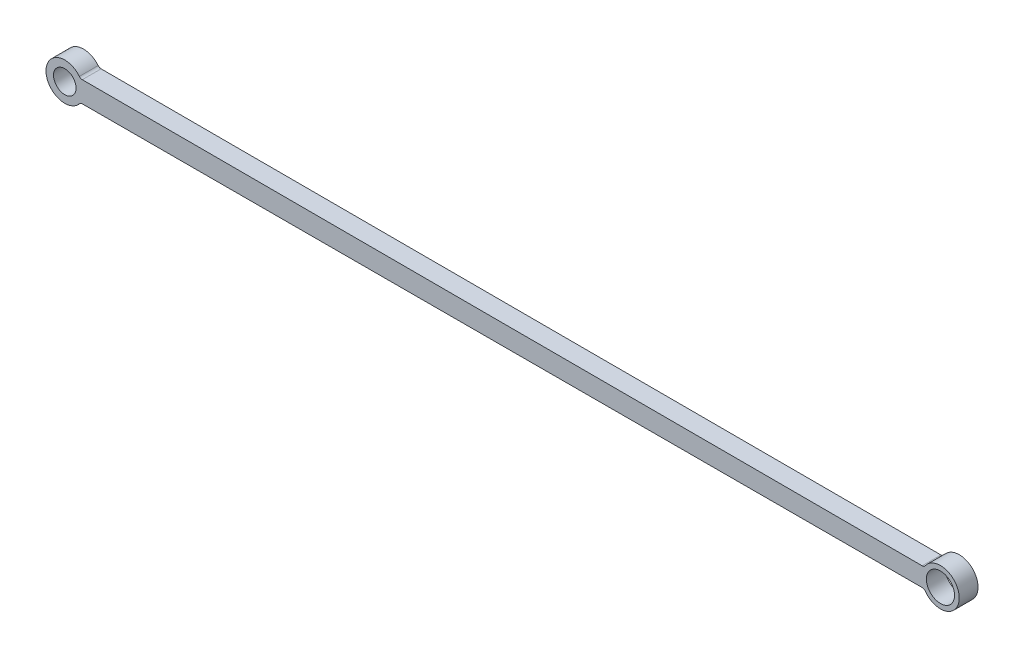
SolidWorks part; units mm, degrees
ref_plane "Plano frontal" through (0, 0, 0) normal (0, 0, 1) x (1, 0, 0)
ref_plane "Plano superior" through (0, 0, 0) normal (0, 1, 0) x (1, 0, 0)
ref_plane "Plano direito" through (0, 0, 0) normal (1, 0, 0) x (0, 0, -1)
sketch "Esboço1" plane through (0, 0, 0) normal (0, 0, 1) x (1, 0, 0)
  line L0 (-160.8646, 0) -> (280.1062, 0) construction
  line L1 (4.6548, -2.7843) -> (228.1286, -2.5045)
  line L2 (4.6548, 2.7843) -> (228.1286, 2.5045)
  circle A0 centre (0, 0) radius 3
  circle A1 centre (233, 0) radius 3.75
  arc A2 (3.88, 3.1536) -> (3.88, -3.1536) centre (0, 0) ccw
  arc A3 (228.9415, -2.9204) -> (228.9415, 2.9204) centre (233, 0) ccw
  arc A4 (4.6548, 2.7843) -> (3.88, 3.1536) centre (4.656, 3.7843) cw
  arc A5 (4.6548, -2.7843) -> (3.88, -3.1536) centre (4.656, -3.7843) ccw
  arc A6 (228.1286, 2.5045) -> (228.9415, 2.9204) centre (228.1298, 3.5045) ccw
  arc A7 (228.9415, -2.9204) -> (228.1286, -2.5045) centre (228.1298, -3.5045) ccw
  point P13 (4.1526, 2.785)
  point P16 (4.1526, -2.785)
  point P19 (228.6721, 2.5038)
  point P22 (228.6721, -2.5038)
  dimension "D2" = 6
  dimension "D3" = 10
  dimension "D4" = 7.5
  dimension "D5" = 10
  dimension "D6" = 1
  dimension "D7" = 1
  dimension "D8" = 1
  dimension "D9" = 1
  dimension "D1" = 233
extrude "Ressalto-extrusão1" add sketch "Esboço1" along normal blind 5
